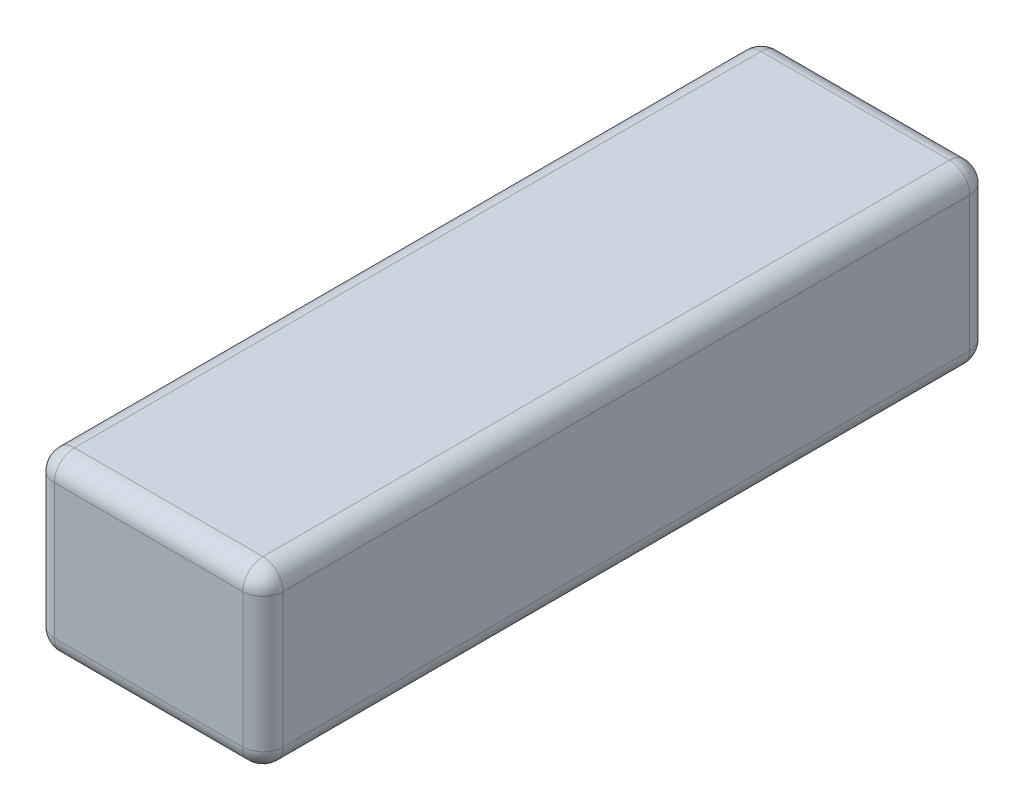
SolidWorks part; units mm, degrees
ref_plane "Front Plane" through (0, 0, 0) normal (0, 0, 1) x (1, 0, 0)
ref_plane "Top Plane" through (0, 0, 0) normal (0, 1, 0) x (1, 0, 0)
ref_plane "Right Plane" through (0, 0, 0) normal (1, 0, 0) x (0, 0, -1)
sketch "Sketch1" plane through (0, 0, 0) normal (1, 0, 0) x (0, 0, -1)
  line L0 (-51, 10) -> (51, -10) construction
  line L1 (-51, 13) -> (51, 13)
  line L2 (-54, 10) -> (-54, -10)
  line L3 (-51, -13) -> (51, -13)
  line L4 (54, 10) -> (54, -10)
  arc A0 (51, 13) -> (54, 10) centre (51, 10) cw
  arc A1 (51, -13) -> (54, -10) centre (51, -10) ccw
  arc A2 (-54, -10) -> (-51, -13) centre (-51, -10) ccw
  arc A3 (-51, 13) -> (-54, 10) centre (-51, 10) ccw
  dimension "D3" = 3
  dimension "D1" = 108
  dimension "D2" = 26
extrude "Boss-Extrude1" add sketch "Sketch1" along normal mid plane 34
fillet "Fillet1" radius 3 16 edges at (-17, 13, 0) (-17, 12.1213, 53.1213) (-17, 0, 54) (-17, -12.1213, 53.1213) (-17, -13, 0) (-17, -12.1213, -53.1213) (-17, 0, -54) (-17, 12.1213, -53.1213) (17, 0, -54) (17, -12.1213, -53.1213) (17, -13, 0) (17, -12.1213, 53.1213) (17, 0, 54) (17, 12.1213, 53.1213) (17, 13, 0) (17, 12.1213, -53.1213)
